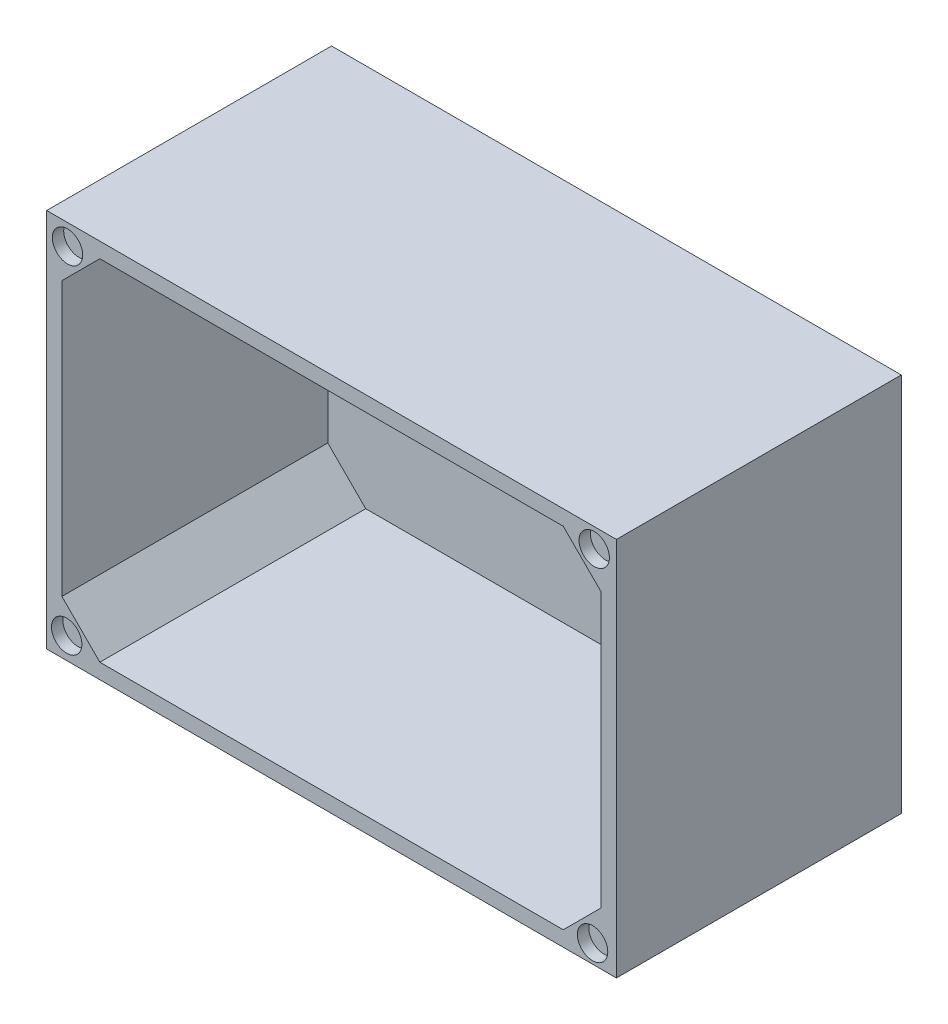
SolidWorks part; units mm, degrees
ref_plane "Plan de face" through (0, 0, 0) normal (0, 0, 1) x (1, 0, 0)
ref_plane "Plan de dessus" through (0, 0, 0) normal (0, 1, 0) x (1, 0, 0)
ref_plane "Plan de droite" through (0, 0, 0) normal (1, 0, 0) x (0, 0, -1)
sketch "Esquisse1" plane through (0, 0, 0) normal (0, 0, 1) x (1, 0, 0)
  line L1 (-51.1936, 0) -> (98.8064, 0)
  line L2 (-51.1936, 0) -> (-51.1936, -100)
  line L3 (-51.1936, -100) -> (98.8064, -100)
  line L4 (98.8064, 0) -> (98.8064, -100)
  dimension "D1" = 150
  dimension "D2" = 100
extrude "Boss.-Extru.1" add sketch "Esquisse1" along normal blind 75
sketch "Esquisse2" plane through (0, 0, 75) normal (0, 0, 1) x (1, 0, 0)
  line L1 (-37.1936, -4) -> (84.8064, -4)
  line L2 (-47.1936, -14) -> (-47.1936, -86)
  line L3 (-37.1936, -96) -> (84.8064, -96)
  line L4 (94.8064, -14) -> (94.8064, -86)
  line L6 (-47.1936, -14) -> (-37.1936, -4)
  line L7 (84.8064, -4) -> (94.8064, -14)
  line L8 (84.8064, -96) -> (94.8064, -86)
  line L9 (-47.1936, -86) -> (-37.1936, -96)
  point P0 (-47.1936, -4)
  point P1 (94.8064, -96)
  point P2 (-47.1936, -96)
  point P3 (94.8064, -4)
extrude "Enlèv. mat.-Extru.2" cut sketch "Esquisse2" against normal blind 70 contours L2 L9 L3 L8 L4 L7 L1 L6
sketch "Esquisse5" plane through (0, 0, 75) normal (0, 0, 1) x (1, 0, 0)
  line L0 (-47.1936, -14) -> (-37.1936, -4) construction
  circle A0 centre (-45.7115, -5.447) radius 4
  point P0 (-42.1936, -9)
  dimension "D1" = 5
extrude "Enlèv. mat.-Extru.3" cut sketch "Esquisse5" against normal blind 3 contours A0
sketch "Esquisse6" plane through (0, 0, 75) normal (0, 0, 1) x (1, 0, 0)
  line L0 (84.8064, -4) -> (94.8064, -14) construction
  line L1 (84.8064, -96) -> (94.8064, -86) construction
  line L2 (-47.1936, -86) -> (-37.1936, -96) construction
  circle A0 centre (92.9548, -5.1157) radius 4
  circle A1 centre (92.526, -95.1957) radius 4
  circle A3 centre (-45.931, -94.3214) radius 4
  point P0 (89.8064, -9)
  point P1 (89.8064, -91)
  point P4 (-42.1936, -91)
  dimension "D1" = 5
  dimension "D3" = 5
  dimension "D2" = 5
extrude "Enlèv. mat.-Extru.4" cut sketch "Esquisse6" against normal blind 3
